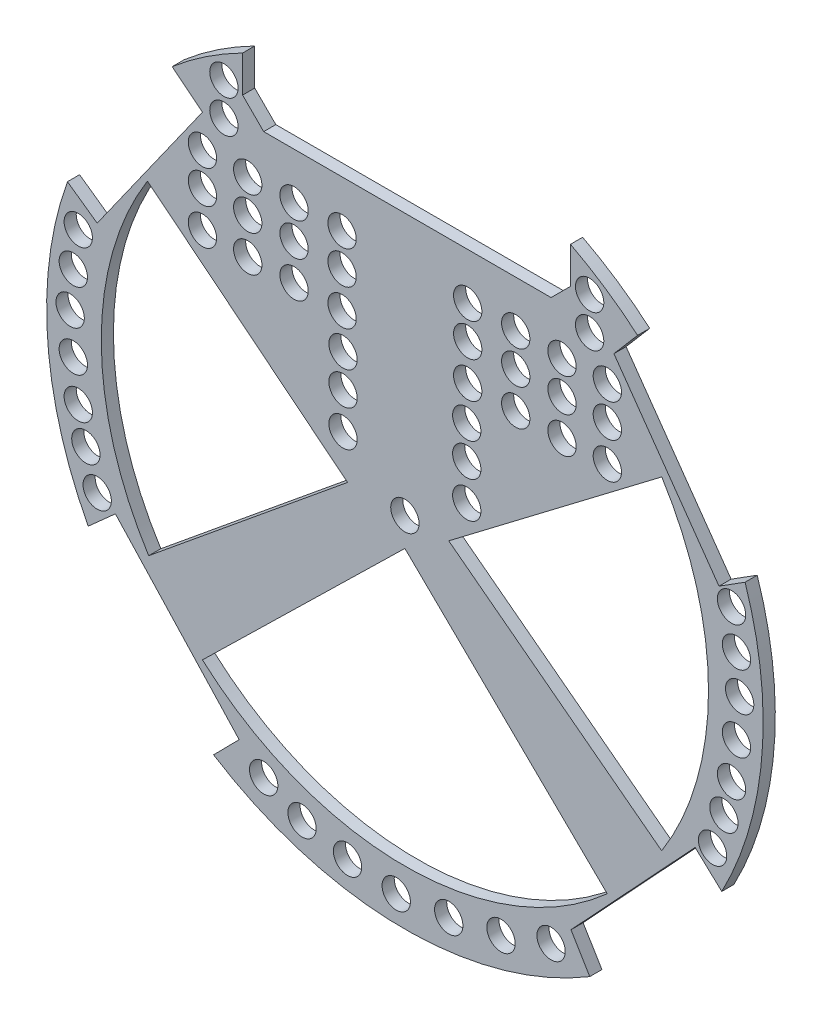
SolidWorks part; units mm, degrees
ref_plane "Front Plane" through (0, 0, 0) normal (0, 0, 1) x (1, 0, 0)
ref_plane "Top Plane" through (0, 0, 0) normal (0, 1, 0) x (1, 0, 0)
ref_plane "Right Plane" through (0, 0, 0) normal (1, 0, 0) x (0, 0, -1)
sketch "Sketch1" plane through (0, 0, 0) normal (0, 0, 1) x (1, 0, 0)
  line L1 (40.9072, 78.4783) -> (40.9072, 69.4783)
  line L2 (-40.0917, 78.8981) -> (-40.0917, 69.8981)
  line L3 (-34.8824, 64.6887) -> (36.1176, 64.6887)
  line L4 (-34.8824, 64.6887) -> (-40.0917, 69.8981)
  line L5 (36.1176, 64.6887) -> (40.9072, 69.4783)
  line L6 (45.6721, -75.8044) -> (41.0275, -68.0955)
  line L7 (-57.4843, 67.289) -> (-50.0106, 61.2716)
  line L8 (-50.0106, 61.2716) -> (-76.0072, 24.5405)
  line L9 (-76.0072, 24.5405) -> (-83.3534, 29.7398)
  line L11 (57.4843, 67.289) -> (51.6384, 60.446)
  line L12 (51.6384, 60.446) -> (77.5923, 23.6847)
  line L13 (77.5923, 23.6847) -> (84.0359, 27.7528)
  line L14 (41.0275, -68.0955) -> (71.6896, -35.1587)
  line L15 (71.6896, -35.1587) -> (78.277, -41.2912)
  line L16 (-71.5124, -35.3951) -> (-78.2242, -41.3911)
  line L17 (-71.5124, -35.3951) -> (-40.9408, -68.416)
  line L18 (-40.9408, -68.416) -> (-47.2591, -74.8253)
  line L19 (10.8352, 0) -> (63.4521, 39.9854)
  line L20 (10.8352, 0) -> (63.4337, -40.0146)
  line L22 (0, -7.0434) -> (-50.0133, -55.8898)
  line L23 (0, -7.0434) -> (49.9867, -55.9136)
  line L24 (-14.1627, 0) -> (-63.2891, -40.2428)
  line L25 (-14.1627, 0) -> (-63.5953, 39.7572)
  line L27 (0, -92.0689) -> (0, 92.0689) construction
  arc A0 (-40.0917, 78.8981) -> (-57.4843, 67.289) centre (0, 0) ccw
  arc A1 (57.4843, 67.289) -> (40.9072, 78.4783) centre (0, 0) ccw
  arc A2 (-83.3534, 29.7398) -> (-78.2242, -41.3911) centre (0, 0) ccw
  arc A3 (78.277, -41.2912) -> (84.0359, 27.7528) centre (0, 0) ccw
  arc A4 (-47.2591, -74.8253) -> (45.6721, -75.8044) centre (0, 0) ccw
  arc A5 (-63.5953, 39.7572) -> (-63.2891, -40.2428) centre (0, 0) ccw
  arc A6 (63.4337, -40.0146) -> (63.4521, 39.9854) centre (0, 0) ccw
  arc A7 (-50.0133, -55.8898) -> (49.9867, -55.9136) centre (0, 0) ccw
  circle A8 centre (-50.0106, 36.0278) radius 3.5
  circle A9 centre (-50.0106, 44.9656) radius 3.5
  circle A10 centre (-50.0106, 53.1373) radius 3.5
  circle A11 centre (-38.8181, 35.8978) radius 3.5
  circle A12 centre (-38.8181, 44.8356) radius 3.5
  circle A13 centre (-38.8181, 53.0074) radius 3.5
  circle A14 centre (-27.3803, 36.073) radius 3.5
  circle A15 centre (-27.3803, 45.0108) radius 3.5
  circle A16 centre (-27.3803, 53.1825) radius 3.5
  circle A17 centre (-15.52, 36.039) radius 3.5
  circle A18 centre (-15.52, 44.9769) radius 3.5
  circle A19 centre (-15.52, 53.1486) radius 3.5
  circle A20 centre (-15.2861, 10.2863) radius 3.5
  circle A21 centre (-15.2861, 19.2241) radius 3.5
  circle A22 centre (-15.2861, 27.3958) radius 3.5
  circle A23 centre (15.2861, 27.3958) radius 3.5
  circle A24 centre (15.2861, 19.2241) radius 3.5
  circle A25 centre (15.2861, 10.2863) radius 3.5
  circle A26 centre (15.52, 53.1486) radius 3.5
  circle A27 centre (15.52, 44.9769) radius 3.5
  circle A28 centre (15.52, 36.039) radius 3.5
  circle A29 centre (27.3803, 53.1825) radius 3.5
  circle A30 centre (27.3803, 45.0108) radius 3.5
  circle A31 centre (27.3803, 36.073) radius 3.5
  circle A32 centre (38.8181, 53.0074) radius 3.5
  circle A33 centre (38.8181, 44.8356) radius 3.5
  circle A34 centre (38.8181, 35.8978) radius 3.5
  circle A35 centre (50.0106, 53.1373) radius 3.5
  circle A36 centre (50.0106, 44.9656) radius 3.5
  circle A37 centre (50.0106, 36.0278) radius 3.5
  circle A38 centre (45.6322, 70.0916) radius 3.5
  circle A39 centre (45.6322, 61.9199) radius 3.5
  circle A40 centre (-44.707, 70.8051) radius 3.5
  circle A41 centre (-44.707, 62.6334) radius 3.5
  circle A42 centre (-80.6839, 20.8061) radius 3.5
  circle A43 centre (-81.9064, 11.7509) radius 3.5
  circle A44 centre (-82.6962, 2.6118) radius 3.5
  circle A45 centre (-81.9064, -7.0434) radius 3.5
  circle A46 centre (-80.6839, -16.5928) radius 3.5
  circle A47 centre (-78.807, -24.6877) radius 3.5
  circle A48 centre (-76.0072, -33.1473) radius 3.5
  circle A49 centre (76.0072, -33.1473) radius 3.5
  circle A50 centre (78.807, -24.6877) radius 3.5
  circle A51 centre (80.6839, -16.5928) radius 3.5
  circle A52 centre (81.9064, -7.0434) radius 3.5
  circle A53 centre (82.6962, 2.6118) radius 3.5
  circle A54 centre (81.9064, 11.7509) radius 3.5
  circle A55 centre (80.6839, 20.8061) radius 3.5
  circle A56 centre (-34.8824, -73.506) radius 3.5
  circle A57 centre (-25.3998, -77.9738) radius 3.5
  circle A58 centre (-2.1362, -81.9795) radius 3.5
  circle A59 centre (0, 0) radius 3.5
  circle A60 centre (-14.1627, -80.5929) radius 3.5
  circle A61 centre (10.8352, -80.5929) radius 3.5
  circle A62 centre (23.7465, -77.9738) radius 3.5
  circle A63 centre (36.1176, -73.506) radius 3.5
  point P105 (-81.2818, 20.5875)
  point P106 (-82.0583, 19.2241)
  point P107 (-80.8675, 19.2241)
  point P110 (-81.9064, 9.5379)
  point P113 (-81.9064, -0.8513)
  point P116 (-80.1402, -10.9289)
  point P117 (-80.1402, 19.2241)
  point P118 (-80.6839, 20.8061)
  point P119 (-81.9064, 11.7509)
  point P120 (-82.6962, 2.6118)
  point P121 (-81.9064, -7.0434)
  point P124 (-80.6839, -15.6991)
  point P125 (-80.6839, -16.5928)
  point P128 (-78.807, -25.7155)
  point P131 (-76.0072, -33.1473)
  point P132 (-78.807, -24.6877)
  point P133 (0, 0)
  point P150 (-38.8181, -73.6601)
  point P153 (-28.481, -78.282)
  point P156 (0, -81.8254)
  point P161 (-12.6125, -79.8226)
  point P162 (0, -82.2876)
  point P163 (-13.2288, -80.5929)
  point P164 (0, 0)
  point P165 (-25.3998, -77.9738)
  point P166 (-34.8824, -73.506)
  point P169 (10.8352, -80.5929)
  point P170 (-14.1627, -80.5929)
  point P171 (10.8352, -80.5929)
  point P172 (-2.1362, -81.9795)
  point P175 (23.7465, -77.0929)
  point P178 (36.1176, -73.506)
  dimension "D16" = 150
  dimension "D2" = 81
  dimension "D3" = 9
  dimension "D4" = 9
  dimension "D5" = 71
  dimension "D6" = 9
  dimension "D7" = 9
  dimension "D8" = 45
  dimension "D9" = 9
  dimension "D10" = 45
  dimension "D11" = 9
  dimension "D12" = 45
  dimension "D13" = 9
  dimension "D14" = 45
  dimension "D15" = 9
  dimension "D17" = 80
  dimension "D18" = 80
  dimension "D19" = 100
extrude "Boss-Extrude4" add sketch "Sketch1" along normal blind 3
